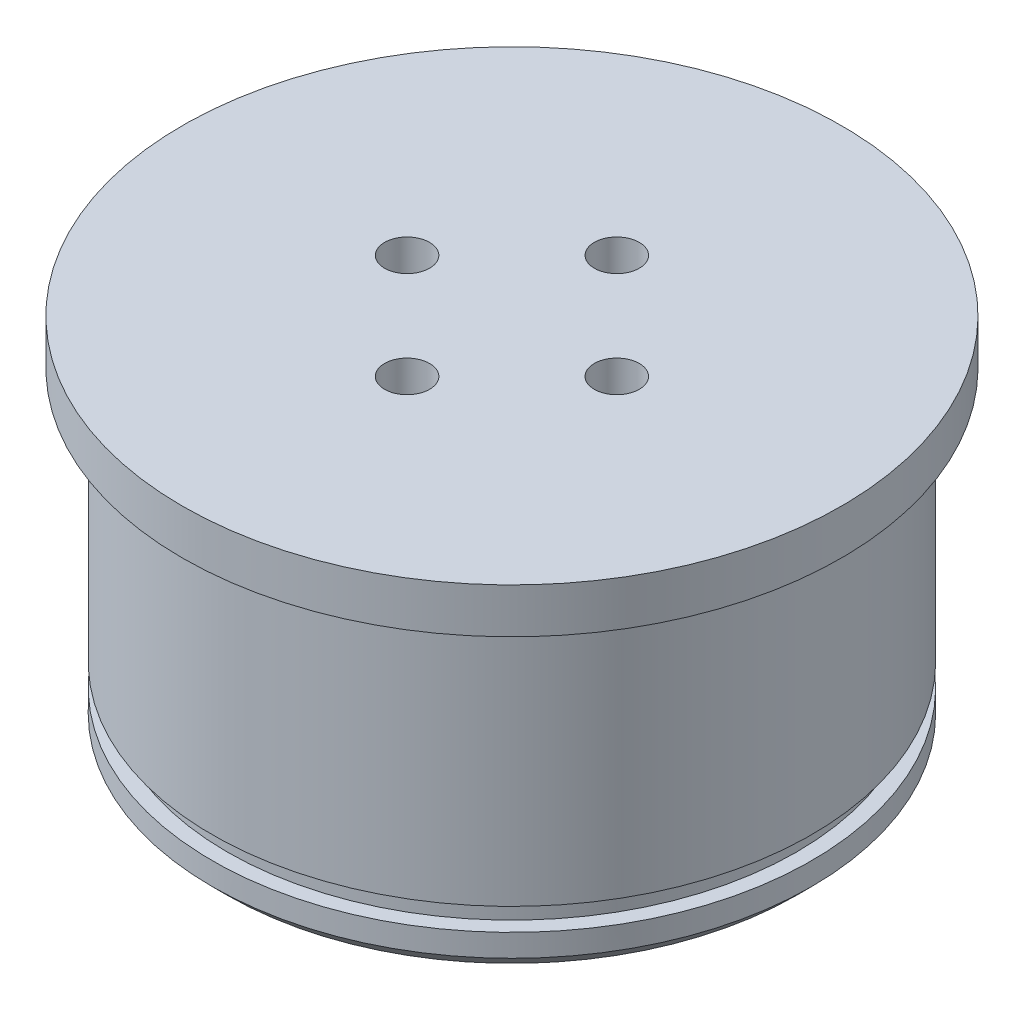
SolidWorks part; units mm, degrees
ref_plane "Спереди" through (0, 0, 0) normal (0, 0, 1) x (1, 0, 0)
ref_plane "Сверху" through (0, 0, 0) normal (0, 1, 0) x (1, 0, 0)
ref_plane "Справа" through (0, 0, 0) normal (1, 0, 0) x (0, 0, -1)
sketch "Эскиз1" plane through (0, 0, 0) normal (0, 1, 0) x (1, 0, 0)
  circle A0 centre (0, 0) radius 20
  dimension "D1" = 40
extrude "Бобышка-Вытянуть1" add sketch "Эскиз1" along normal blind 21
sketch "Эскиз2" plane through (0, 0, 0) normal (0, -1, 0) x (1, 0, 0)
  circle A0 centre (0, 0) radius 10
  dimension "D1" = 20
extrude "Вырез-Вытянуть2" cut sketch "Эскиз2" against normal blind 2.5
ref_plane "Плоскость1" through (0, 2.5, 0) normal (0, -1, 0) x (-1, 0, 0)
sketch "Эскиз5" plane through (0, 2.5, 0) normal (0, -1, 0) x (-1, 0, 0)
  circle A0 centre (0, 0) radius 19
  circle A1 centre (0, 0) radius 20
  dimension "D1" = 38
  dimension "D2" = 40
extrude "Вырез-Вытянуть5" cut sketch "Эскиз5" against normal blind 1.5
chamfer "Фаска1" distance 1 angle 45 1 edges at (0, 0, 20)
sketch "Эскиз6" plane through (0, 21, 0) normal (0, 1, 0) x (1, 0, 0)
  circle A0 centre (0, 0) radius 22
  dimension "D1" = 44
extrude "Бобышка-Вытянуть2" add sketch "Эскиз6" along normal blind 3
sketch "Эскиз4" plane through (0, 2.5, 0) normal (0, -1, 0) x (1, 0, 0)
  circle A0 centre (0, 7) radius 1.5
  dimension "D2" = 3
  dimension "D1" = 7
extrude "Вырез-Вытянуть6" cut sketch "Эскиз4" against normal through all
pattern_circular "Круговой массив1" count 4 over 360 about axis through (0, 0, 0) along (0, 1, 0) of "Вырез-Вытянуть6"
